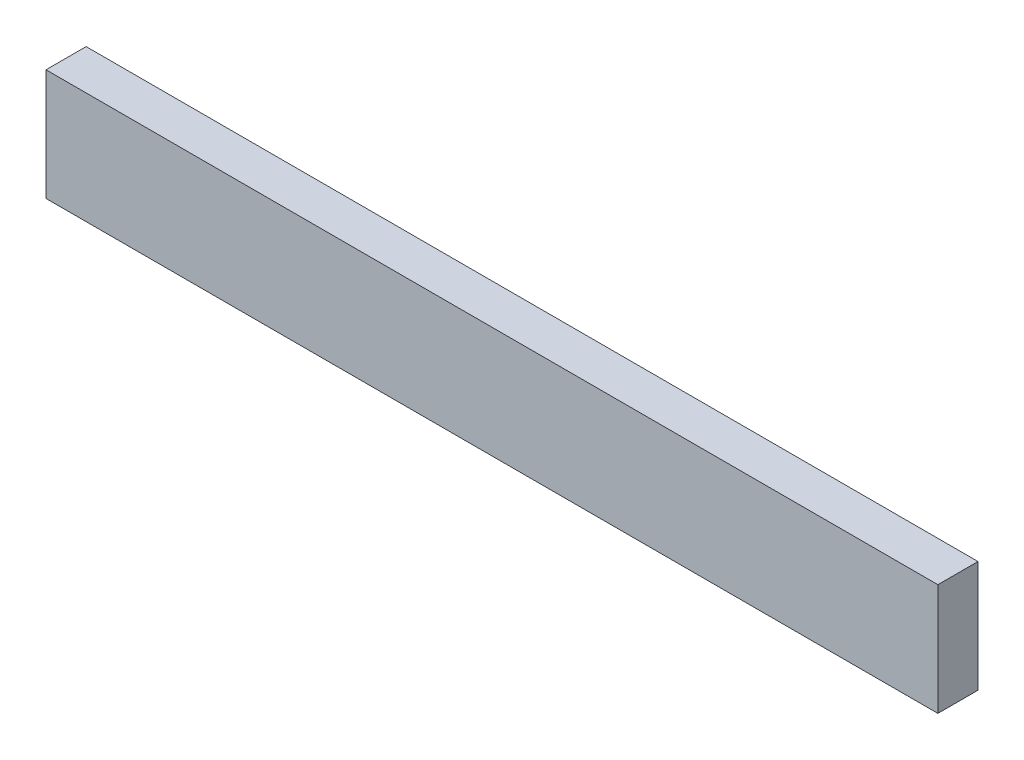
SolidWorks part; units mm, degrees
ref_plane "Front Plane" through (0, 0, 0) normal (0, 0, 1) x (1, 0, 0)
ref_plane "Top Plane" through (0, 0, 0) normal (0, 1, 0) x (1, 0, 0)
ref_plane "Right Plane" through (0, 0, 0) normal (1, 0, 0) x (0, 0, -1)
sketch "Sketch2" plane through (0, 0, 0) normal (0, 0, 1) x (1, 0, 0)
  line L1 (0, 0) -> (400, 0)
  line L2 (0, 0) -> (0, 50)
  line L3 (0, 50) -> (400, 50)
  line L4 (400, 0) -> (400, 50)
  dimension "D1" = 400
  dimension "D2" = 50
extrude "Boss-Extrude1" add sketch "Sketch2" along normal blind 18
